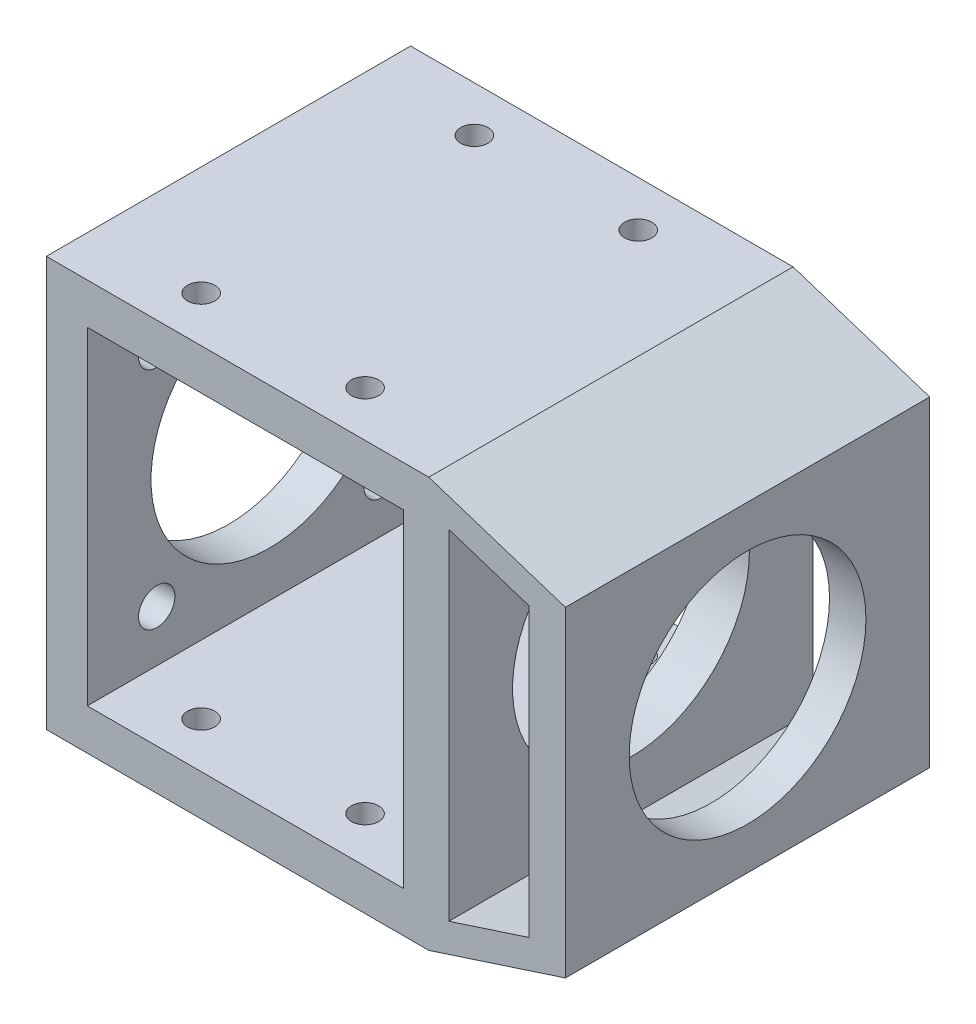
SolidWorks part; units mm, degrees
material "6061 合金"
ref_plane "前视基准面" through (0, 0, 0) normal (0, 0, 1) x (1, 0, 0)
ref_plane "上视基准面" through (0, 0, 0) normal (0, 1, 0) x (1, 0, 0)
ref_plane "右视基准面" through (0, 0, 0) normal (1, 0, 0) x (0, 0, -1)
sketch "草图1" plane through (0, 0, 0) normal (0, 1, 0) x (1, 0, 0)
  line L1 (-57, 20) -> (0, 20)
  line L2 (-57, 20) -> (-57, -20)
  line L3 (-57, -20) -> (0, -20)
  line L4 (0, 20) -> (0, -20)
  dimension "D1" = 57
  dimension "D2" = 40
  dimension "D3" = 40
  dimension "D4" = 57
extrude "凸台-拉伸1" add sketch "草图1" along normal blind 45
sketch "草图5" plane through (0, 0, 0) normal (1, 0, 0) x (0, 0, -1)
  line L1 (-20, 22.5) -> (20, 22.5) construction
  line L2 (-20, 45) -> (-20, 0) construction
  line L3 (20, 45) -> (20, 0) construction
  circle A0 centre (0, 22.5) radius 13
  dimension "D1" = 26
extrude "切除-拉伸1" cut sketch "草图5" against normal blind 17.8
sketch "草图6" plane through (-17.8, 0, 0) normal (1, 0, 0) x (0, 0, -1)
  line L0 (-22, 25) -> (-22, 3)
  line L5 (-22, 3) -> (22, 3)
  line L6 (22, 25) -> (22, 3)
  line L7 (-20, 45) -> (20, 45) construction
  line L8 (-22, 25) -> (-22, 42)
  line L9 (-22, 42) -> (22, 42)
  line L10 (22, 42) -> (22, 25)
  line L11 (20, 0) -> (-20, 0) construction
  dimension "D1" = 44
  dimension "D2" = 3
  dimension "D3" = 3
  dimension "D4" = 44
extrude "切除-拉伸2" cut sketch "草图6" against normal blind 36.2
sketch "草图7" plane through (-54, 0, 0) normal (1, 0, 0) x (0, 0, -1)
  line L1 (20, 22.5) -> (-20, 22.5) construction
  line L2 (20, 42) -> (20, 3) construction
  line L3 (-20, 3) -> (-20, 42) construction
  circle A0 centre (0, 22.5) radius 13
  dimension "D1" = 26
extrude "切除-拉伸3" cut sketch "草图7" against normal blind 31.1
sketch "草图10" plane through (0, 0, 20) normal (0, 0, 1) x (1, 0, 0)
  line L0 (-15, 45) -> (0, 40.1262)
  line L1 (-57, 45) -> (0, 45) construction
  line L2 (0, 45) -> (0, 0) construction
  line L3 (-15, 45) -> (0, 45)
  line L4 (0, 45) -> (0, 40.1262)
  line L5 (0, 0) -> (-15, 0)
  line L6 (-57, 0) -> (0, 0) construction
  line L7 (-15, 0) -> (0, 4.8738)
  line L8 (0, 4.8738) -> (0, 0)
  dimension "D4" = 18
  dimension "D1" = 18
  dimension "D2" = 15
  dimension "D3" = 15
extrude "切除-拉伸5" cut sketch "草图10" against normal through all
sketch "草图12" plane through (-57, 0, 0) normal (-1, 0, 0) x (0, 0, 1)
  line L0 (-12.3744, 34.8744) -> (0, 22.5) construction
  line L1 (0, 22.5) -> (0, 40) construction
  circle A0 centre (0, 22.5) radius 17.5 construction
  circle A1 centre (-12.3744, 34.8744) radius 2
  circle A2 centre (12.3744, 34.8744) radius 2
  circle A3 centre (12.3744, 10.1256) radius 2
  circle A4 centre (-12.3744, 10.1256) radius 2
  point P15 (0, 22.5)
  dimension "D1" = 35
  dimension "D2" = 4
  dimension "D3" = 45
  dimension "D4" = 4
extrude "切除-拉伸6" cut sketch "草图12" against normal blind 8
sketch "草图13" plane through (0, 45, 0) normal (0, 1, 0) x (1, 0, 0)
  circle A0 centre (-45, 15) radius 1.5
  circle A1 centre (-27, 15) radius 1.5
  circle A2 centre (-27, -15) radius 1.5
  circle A3 centre (-45, -15) radius 1.5
  dimension "D1" = 3
  dimension "D2" = 3
  dimension "D3" = 3
  dimension "D4" = 3
extrude "切除-拉伸7" cut sketch "草图13" against normal through all
sketch "草图15" plane through (0, 0, 20) normal (0, 0, 1) x (1, 0, 0)
  line L0 (-13.8, 41.4557) -> (-4, 38.2715)
  line L1 (-4, 38.2715) -> (-4, 6.7285)
  line L2 (-4, 6.7285) -> (-13.8, 3.5443)
  line L3 (-13.8, 3.5443) -> (-13.8, 41.4557)
  line L4 (-15, 45) -> (0, 40.1262) construction
  line L5 (0, 40.1262) -> (0, 4.8738) construction
  line L6 (-17.8, 3) -> (-17.8, 42) construction
  line L7 (0, 4.8738) -> (-15, 0) construction
  dimension "D1" = 4
  dimension "D2" = 4
  dimension "D3" = 3
  dimension "D4" = 3
extrude "切除-拉伸9" cut sketch "草图15" against normal blind 94
sketch "草图16" plane through (-54, 0, 0) normal (1, 0, 0) x (0, 0, -1)
  line L4 (-20, 3) -> (20, 3)
  line L5 (20, 3) -> (20, 42)
  line L6 (20, 42) -> (-20, 42)
  line L7 (-20, 42) -> (-20, 3)
  line L8 (-20, 3) -> (20, 3)
  line L9 (20, 3) -> (20, 42)
  line L10 (20, 42) -> (-20, 42)
  line L11 (-20, 42) -> (-20, 3)
  circle A0 centre (-12.3744, 10.1256) radius 2 construction
  circle A1 centre (12.3744, 10.1256) radius 2 construction
  circle A2 centre (0, 22.5) radius 13 construction
  circle A3 centre (12.3744, 34.8744) radius 2 construction
  circle A4 centre (-12.3744, 34.8744) radius 2 construction
  circle A5 centre (-12.3744, 10.1256) radius 2
  circle A6 centre (12.3744, 10.1256) radius 2
  circle A7 centre (0, 22.5) radius 13
  circle A8 centre (12.3744, 34.8744) radius 2
  circle A9 centre (-12.3744, 34.8744) radius 2
  dimension "D1" = 0
extrude "凸台-拉伸2" add sketch "草图16" along normal blind 1.5
sketch "草图17" plane through (0, 3, 0) normal (0, 1, 0) x (1, 0, 0)
  line L4 (-17.8, 20) -> (-52.5, 20)
  line L5 (-52.5, 20) -> (-52.5, -20)
  line L6 (-52.5, -20) -> (-17.8, -20)
  line L7 (-17.8, -20) -> (-17.8, 20)
  line L8 (-17.8, 20) -> (-52.5, 20)
  line L9 (-52.5, 20) -> (-52.5, -20)
  line L10 (-52.5, -20) -> (-17.8, -20)
  line L11 (-17.8, -20) -> (-17.8, 20)
  circle A0 centre (-45, -15) radius 1.5 construction
  circle A1 centre (-27, -15) radius 1.5 construction
  circle A2 centre (-27, 15) radius 1.5 construction
  circle A3 centre (-45, 15) radius 1.5 construction
  circle A4 centre (-45, -15) radius 1.5
  circle A5 centre (-27, -15) radius 1.5
  circle A6 centre (-27, 15) radius 1.5
  circle A7 centre (-45, 15) radius 1.5
  dimension "D1" = 0
extrude "凸台-拉伸3" add sketch "草图17" along normal blind 1.5
sketch "草图18" plane through (0, 42, 0) normal (0, -1, 0) x (1, 0, 0)
  line L4 (-17.8, 20) -> (-52.5, 20)
  line L5 (-52.5, 20) -> (-52.5, -20)
  line L6 (-52.5, -20) -> (-17.8, -20)
  line L7 (-17.8, -20) -> (-17.8, 20)
  line L8 (-17.8, 20) -> (-52.5, 20)
  line L9 (-52.5, 20) -> (-52.5, -20)
  line L10 (-52.5, -20) -> (-17.8, -20)
  line L11 (-17.8, -20) -> (-17.8, 20)
  circle A0 centre (-45, -15) radius 1.5 construction
  circle A1 centre (-27, -15) radius 1.5 construction
  circle A2 centre (-27, 15) radius 1.5 construction
  circle A3 centre (-45, 15) radius 1.5 construction
  circle A4 centre (-45, -15) radius 1.5
  circle A5 centre (-27, -15) radius 1.5
  circle A6 centre (-27, 15) radius 1.5
  circle A7 centre (-45, 15) radius 1.5
  dimension "D1" = 0
extrude "凸台-拉伸4" add sketch "草图18" along normal blind 1.5
sketch "草图20" plane through (-13.8, 0, 0) normal (1, 0, 0) x (0, 0, -1)
  line L4 (20, 41.4557) -> (-20, 41.4557)
  line L5 (-20, 41.4557) -> (-20, 3.5443)
  line L6 (-20, 3.5443) -> (20, 3.5443)
  line L7 (20, 3.5443) -> (20, 41.4557)
  line L8 (20, 41.4557) -> (-20, 41.4557)
  line L9 (-20, 41.4557) -> (-20, 3.5443)
  line L10 (-20, 3.5443) -> (20, 3.5443)
  line L11 (20, 3.5443) -> (20, 41.4557)
  circle A0 centre (0, 22.5) radius 13 construction
  circle A1 centre (0, 22.5) radius 13
  dimension "D1" = 0
extrude "凸台-拉伸6" add sketch "草图20" along normal blind 1
